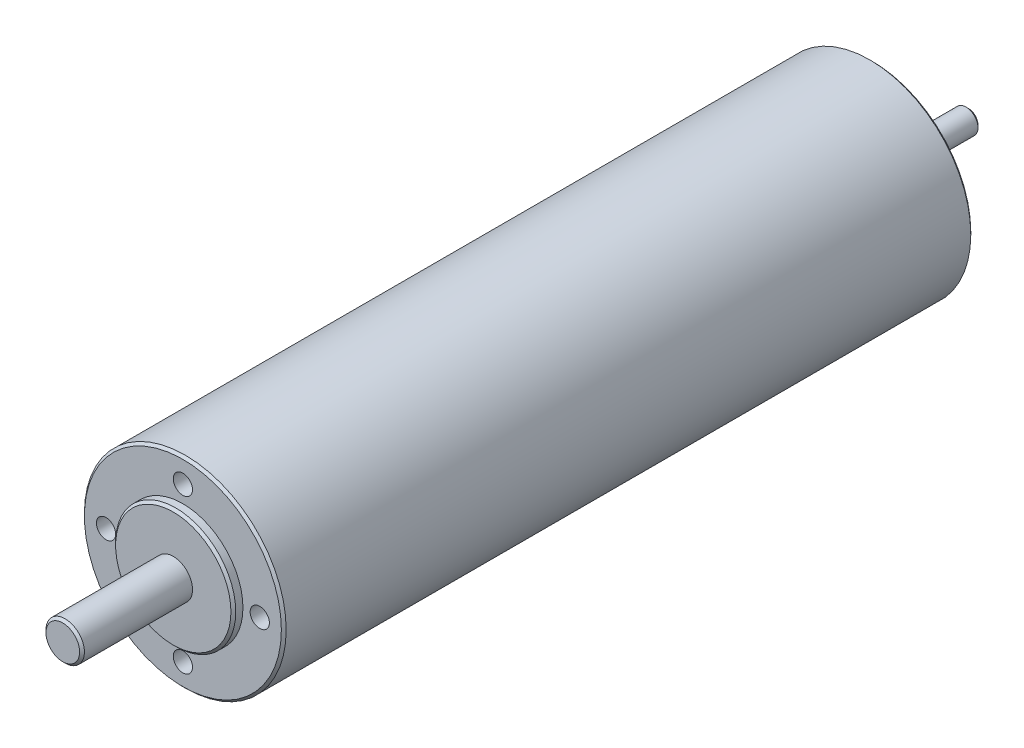
SolidWorks part; units mm, degrees
ref_plane "Face" through (0, 0, 0) normal (0, 0, 1) x (1, 0, 0)
ref_plane "Dessus" through (0, 0, 0) normal (0, 1, 0) x (1, 0, 0)
ref_plane "Droite" through (0, 0, 0) normal (1, 0, 0) x (0, 0, -1)
sketch "Esquisse1" plane through (0, 0, 0) normal (0, 0, 1) x (1, 0, 0)
  circle A0 centre (0, 0) radius 21
  dimension "D1" = 42
extrude "Base-Extrusion" add sketch "Esquisse1" against normal blind 143.5
sketch "Esquisse2" plane through (0, 0, 0) normal (0, 0, 1) x (1, 0, 0)
  circle A0 centre (0, 0) radius 12.5
  dimension "D1" = 25
extrude "Boss.-Extru.1" add sketch "Esquisse2" along normal blind 2
sketch "Esquisse3" plane through (0, 0, 2) normal (0, 0, 1) x (1, 0, 0)
  circle A0 centre (0, 0) radius 4
  dimension "D1" = 8
extrude "Boss.-Extru.2" add sketch "Esquisse3" along normal blind 23
sketch "Esquisse4" plane through (0, 0, -143.5) normal (0, 0, -1) x (-1, 0, 0)
  circle A0 centre (0, 0) radius 11
  dimension "D1" = 22
extrude "Boss.-Extru.3" add sketch "Esquisse4" along normal blind 2
sketch "Esquisse5" plane through (0, 0, -145.5) normal (0, 0, -1) x (-1, 0, 0)
  circle A0 centre (0, 0) radius 2.5
  dimension "D1" = 5
extrude "Boss.-Extru.4" add sketch "Esquisse5" along normal blind 18
chamfer "Chanfrein1" distance 0.5 angle 45 2 edges at (4, 0, 25) (-2.5, 0, -163.5)
sketch "Sketch1" plane through (0, 0, 0) normal (0, 0, 1) x (1, 0, 0)
  line L0 (0, 16) -> (0, -16) construction
  line L2 (16, 0) -> (-16, 0) construction
  circle A0 centre (0, 16) radius 2
  circle A1 centre (16, 0) radius 2
  circle A2 centre (0, -16) radius 2
  circle A3 centre (-16, 0) radius 2
  circle A4 centre (0, 0) radius 16 construction
  point P0 (0, 0)
  dimension "D2" = 4
  dimension "D1" = 32
extrude "Extrude1" cut sketch "Sketch1" against normal blind 10
